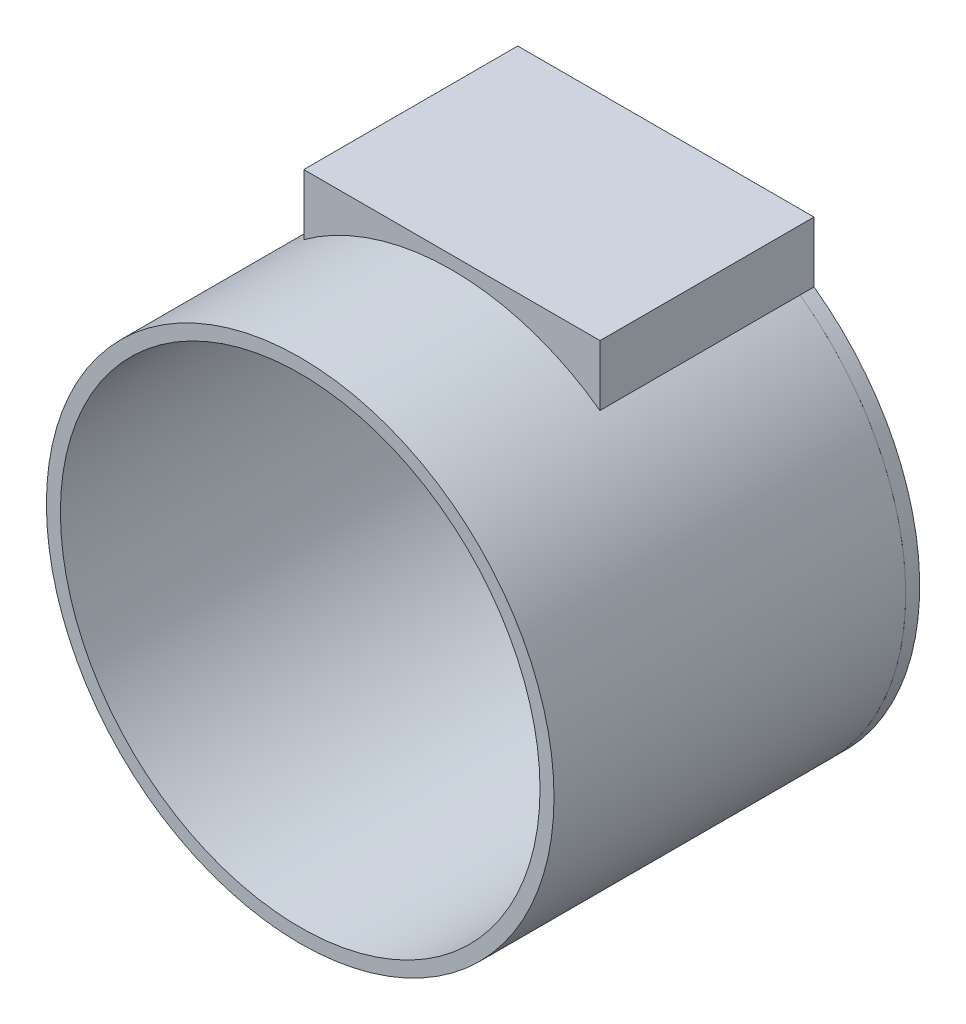
SolidWorks part; units mm, degrees
ref_plane "Plan de face" through (0, 0, 0) normal (0, 0, 1) x (1, 0, 0)
ref_plane "Plan de dessus" through (0, 0, 0) normal (0, 1, 0) x (1, 0, 0)
ref_plane "Plan de droite" through (0, 0, 0) normal (1, 0, 0) x (0, 0, -1)
sketch "Esquisse1" plane through (0, 0, 0) normal (0, 0, 1) x (1, 0, 0)
  line L0 (0, 0) -> (0, 50.7171) construction
  line L1 (0, 0) -> (-19.05, 32.9956) construction
  line L2 (25.4, 35.3388) -> (25.4, 45.7188)
  line L3 (0, 0) -> (19.05, 32.9956) construction
  line L4 (-25.4, 35.3388) -> (-25.4, 45.7188)
  line L5 (-25.4, 45.7188) -> (25.4, 45.7188)
  circle A0 centre (0, 0) radius 34
  circle A1 centre (0, 0) radius 43.52
  circle A2 centre (-19.05, 32.9956) radius 1.97
  circle A3 centre (19.05, 32.9956) radius 1.97
  circle A4 centre (38.1, 0) radius 1.97
  circle A5 centre (19.05, -32.9956) radius 1.97
  circle A6 centre (-19.05, -32.9956) radius 1.97
  circle A7 centre (-38.1, 0) radius 1.97
  point P20 (0, 0)
  dimension "D1" = 87.04
  dimension "D2" = 68
  dimension "D5" = 3.94
  dimension "D3" = 30
  dimension "D4" = 38.1
  dimension "D7" = 38.1
  dimension "D8" = 6.35
  dimension "D9" = 60
  dimension "D10" = 2.3432
  dimension "D11" = 10.38
  dimension "D12" = 50.8
  dimension "D6" = 6
extrude "Boss.-Extru.1" add sketch "Esquisse1" along normal blind 2.4 contours A1 A7 A6 A5 A4 A3 A2 A0 | A1 L2 L5 L4
sketch "Esquisse2" plane through (0, 0, 2.4) normal (0, 0, 1) x (1, 0, 0)
  circle A2 centre (0, 0) radius 43.52
  circle A3 centre (0, 0) radius 41.12
  dimension "D1" = 87.04
  dimension "D2" = 82.24
extrude "Boss.-Extru.2" add sketch "Esquisse2" along normal blind 60.3 separate body
sketch "Esquisse3" plane through (0, 0, 2.4) normal (0, 0, 1) x (1, 0, 0)
  line L0 (-25.4, 35.3388) -> (-25.4, 45.7188) construction
  line L1 (25.4, 35.3388) -> (25.4, 45.7188) construction
  line L2 (-25.4, 45.7188) -> (25.4, 45.7188) construction
  line L3 (-25.4, 35.3388) -> (-25.4, 45.7188)
  line L4 (25.4, 35.3388) -> (25.4, 45.7188)
  line L5 (-25.4, 45.7188) -> (25.4, 45.7188)
  line L6 (-25.4, 35.3388) -> (25.4, 35.3388)
extrude "Boss.-Extru.3" add sketch "Esquisse3" along normal blind 34.29
sketch "Esquisse5" plane through (0, 35.3388, 0) normal (0, -1, 0) x (1, 0, 0)
  line L0 (22.9, 34.19) -> (-22.9, 34.19)
  line L1 (-22.9, 34.19) -> (-22.9, 4.9)
  line L2 (-22.9, 4.9) -> (22.9, 4.9)
  line L3 (22.9, 4.9) -> (22.9, 34.19)
extrude "Enlèv. mat.-Extru.2" cut sketch "Esquisse5" against normal blind 9
sketch "Esquisse6" plane through (0, 0, 62.7) normal (0, 0, 1) x (1, 0, 0)
  circle A0 centre (0, 0) radius 41.12 construction
  circle A1 centre (0, 0) radius 41.12
extrude "Enlèv. mat.-Extru.3" cut sketch "Esquisse6" against normal blind 62
